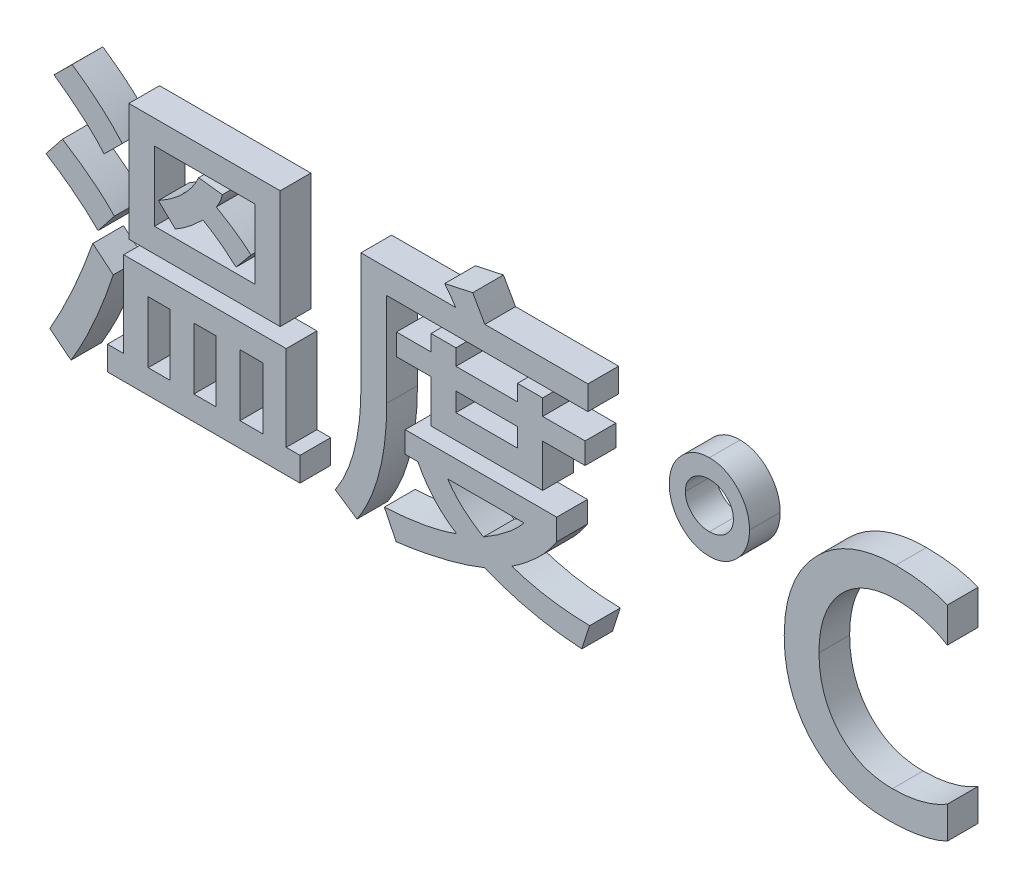
SolidWorks part; units mm, degrees
ref_plane "前基準面" through (0, 0, 0) normal (0, 0, 1) x (1, 0, 0)
ref_plane "上基準面" through (0, 0, 0) normal (0, 1, 0) x (1, 0, 0)
ref_plane "右基準面" through (0, 0, 0) normal (1, 0, 0) x (0, 0, -1)
sketch "草圖1" plane through (0, 0, 0) normal (0, 0, 1) x (1, 0, 0)
  text T0 "溫度" font "微軟正黑體" height 25
extrude "填料-伸長1" add sketch "草圖1" along normal blind 3.5
sketch "草圖2" plane through (0, 0, 3.5) normal (0, 0, 1) x (1, 0, 0)
  text T0 "°C" font "微軟正黑體" height 25
extrude "填料-伸長2" add sketch "草圖2" against normal blind 3.5 separate body
